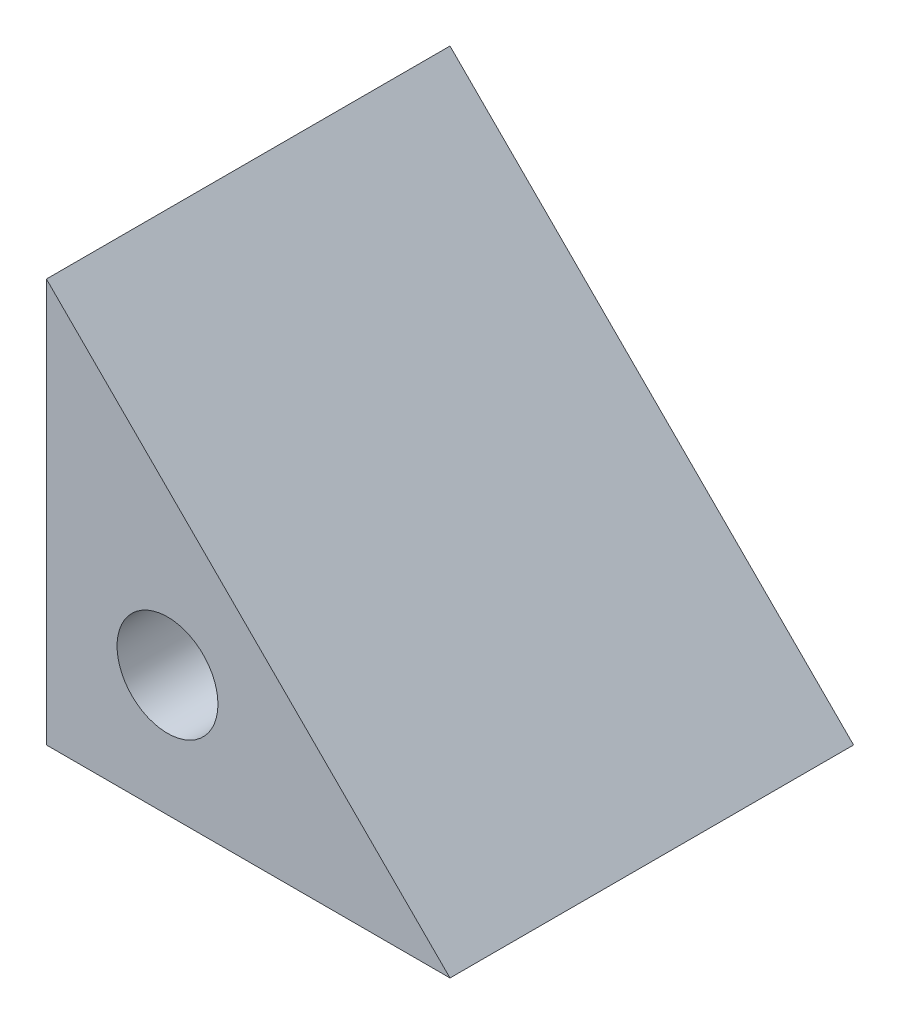
SolidWorks part; units mm, degrees
ref_plane "Спереди" through (0, 0, 0) normal (0, 0, 1) x (1, 0, 0)
ref_plane "Сверху" through (0, 0, 0) normal (0, 1, 0) x (1, 0, 0)
ref_plane "Справа" through (0, 0, 0) normal (1, 0, 0) x (0, 0, -1)
sketch "Эскиз1" plane through (0, 0, 0) normal (0, 0, 1) x (1, 0, 0)
  line L0 (0, 0) -> (0, 40)
  line L1 (0, 40) -> (40, 0)
  line L2 (40, 0) -> (0, 0)
  circle A0 centre (12, 12) radius 5
  dimension "D3" = 10
  dimension "D1" = 40
  dimension "D2" = 40
  dimension "D4" = 12
  dimension "D5" = 12
extrude "Кререж каретки боковой панели" add sketch "Эскиз1" along normal blind 40
